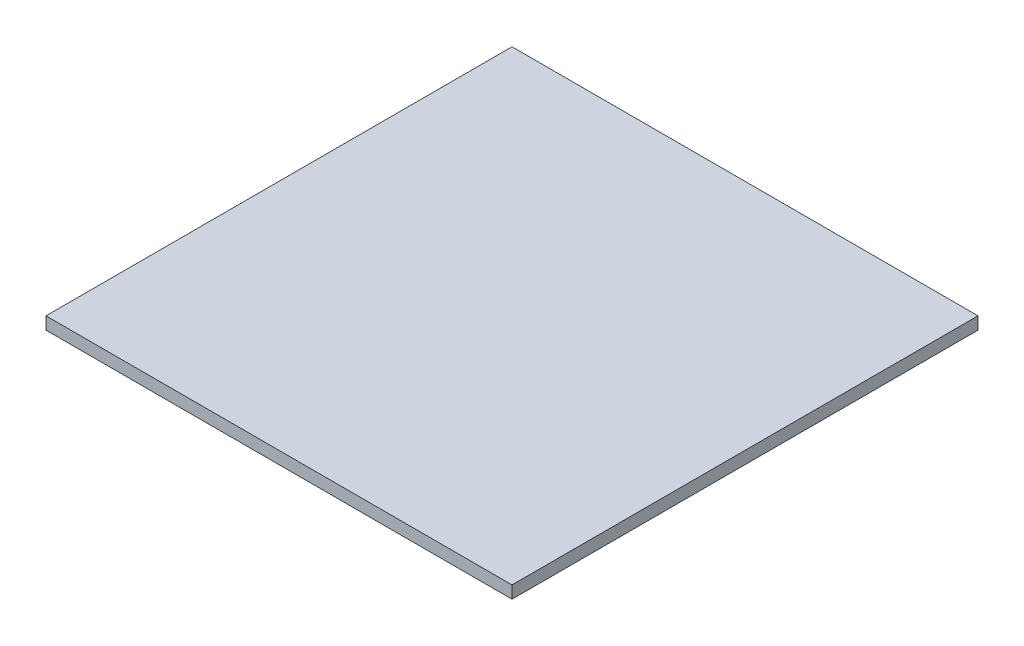
SolidWorks part; units mm, degrees
ref_plane "正面" through (0, 0, 0) normal (0, 0, 1) x (1, 0, 0)
ref_plane "平面" through (0, 0, 0) normal (0, 1, 0) x (1, 0, 0)
ref_plane "右側面" through (0, 0, 0) normal (1, 0, 0) x (0, 0, -1)
sketch "ｽｹｯﾁ1" plane through (0, 0, 0) normal (0, 1, 0) x (1, 0, 0)
  line L1 (-225, 225) -> (225, 225)
  line L2 (-225, 225) -> (-225, -225)
  line L3 (-225, -225) -> (225, -225)
  line L4 (225, 225) -> (225, -225)
  point P4 (0, 225)
  point P6 (-225, 0)
  dimension "D1" = 450
extrude "ﾎﾞｽ - 押し出し1" add sketch "ｽｹｯﾁ1" along normal blind 12
